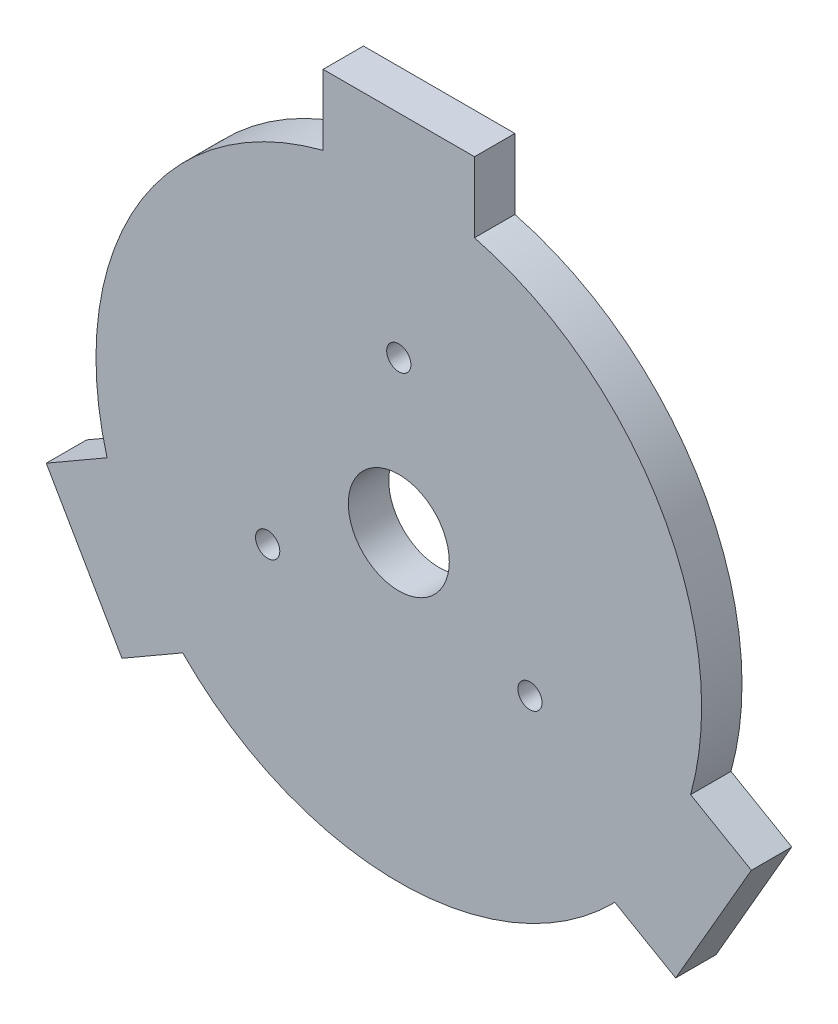
SolidWorks part; units mm, degrees
ref_plane "前视基准面" through (0, 0, 0) normal (0, 0, 1) x (1, 0, 0)
ref_plane "上视基准面" through (0, 0, 0) normal (0, 1, 0) x (1, 0, 0)
ref_plane "右视基准面" through (0, 0, 0) normal (1, 0, 0) x (0, 0, -1)
sketch "草图1" plane through (0, 0, 0) normal (0, 0, 1) x (1, 0, 0)
  line L3 (10, 28.2843) -> (10, 36)
  line L9 (-10, 36) -> (10, 36)
  line L10 (36.1769, -9.3397) -> (26.1769, -26.6603)
  line L11 (-36.1769, -9.3397) -> (-26.1769, -26.6603)
  line L12 (-29.4949, -5.4819) -> (-36.1769, -9.3397)
  line L15 (-19.4949, -22.8024) -> (-26.1769, -26.6603)
  line L17 (19.4949, -22.8024) -> (26.1769, -26.6603)
  line L20 (29.4949, -5.4819) -> (36.1769, -9.3397)
  line L24 (-10, 28.2843) -> (-10, 36)
  arc A1 (-19.4949, -22.8024) -> (19.4949, -22.8024) centre (0, 0) ccw
  circle A2 centre (0, 0) radius 5
  arc A3 (-10, 28.2843) -> (-29.4949, -5.4819) centre (0, 0) ccw
  arc A4 (29.4949, -5.4819) -> (10, 28.2843) centre (0, 0) ccw
  dimension "D10" = 60
  dimension "D2" = 10
extrude "凸台-拉伸1" add sketch "草图1" along normal blind 4
sketch "草图2" plane through (0, 0, 0) normal (0, 0, -1) x (-1, 0, 0)
  line L2 (-7.5, 28.2843) -> (-7.5, 36)
  line L3 (-7.5, 29.0474) -> (-7.5, 36)
  line L4 (-10, 36) -> (10, 36) construction
  line L5 (7.5, 36) -> (7.5, 28.2843)
  line L6 (7.5, 36) -> (7.5, 29.0474)
  line L7 (-10, 36) -> (-7.5, 36)
  line L10 (-34.9269, -11.5048) -> (-28.2449, -7.6469)
  line L11 (-34.9269, -11.5048) -> (-28.9058, -8.0285)
  line L20 (-26.1769, -26.6603) -> (-36.1769, -9.3397) construction
  line L21 (-26.1769, -26.6603) -> (-27.4269, -24.4952)
  line L22 (36.1769, -9.3397) -> (26.1769, -26.6603) construction
  line L23 (36.1769, -9.3397) -> (34.9269, -11.5048)
  line L26 (-20.7449, -20.6373) -> (-27.4269, -24.4952)
  line L27 (-21.4058, -21.0189) -> (-27.4269, -24.4952)
  line L29 (28.2449, -7.6469) -> (34.9269, -11.5048)
  line L30 (28.9058, -8.0285) -> (34.9269, -11.5048)
  line L31 (-10, 36) -> (-10, 28.2843)
  line L32 (27.4269, -24.4952) -> (20.7449, -20.6373)
  line L33 (27.4269, -24.4952) -> (21.4058, -21.0189)
  line L34 (10, 36) -> (10, 28.2843)
  line L35 (-36.1769, -9.3397) -> (-29.4949, -5.4819)
  line L36 (-26.1769, -26.6603) -> (-19.4949, -22.8024)
  line L37 (19.4949, -22.8024) -> (26.1769, -26.6603)
  line L38 (29.4949, -5.4819) -> (36.1769, -9.3397)
  line L39 (7.5, 36) -> (10, 36)
  line L40 (-34.9269, -11.5048) -> (-36.1769, -9.3397)
  line L41 (27.4269, -24.4952) -> (26.1769, -26.6603)
  arc A0 (-7.5, 29.0474) -> (-10, 28.2843) centre (0, 0) ccw
  arc A4 (10, 28.2843) -> (7.5, 29.0474) centre (0, 0) ccw
  arc A5 (-29.4949, -5.4819) -> (-28.9058, -8.0285) centre (0, 0) ccw
  arc A6 (-21.4058, -21.0189) -> (-19.4949, -22.8024) centre (0, 0) ccw
  arc A7 (19.4949, -22.8024) -> (21.4058, -21.0189) centre (0, 0) ccw
  arc A8 (28.9058, -8.0285) -> (29.4949, -5.4819) centre (0, 0) ccw
  dimension "D2" = 2.5
  dimension "D3" = 2.5
  dimension "D4" = 2.5
  dimension "D5" = 2.5
  dimension "D6" = 2.5
  dimension "D7" = 2.5
extrude "切除-拉伸1" cut sketch "草图2" against normal blind 10
sketch "草图3" plane through (0, 0, 0) normal (0, 0, -1) x (-1, 0, 0)
  circle A1 centre (0, 15) radius 1.2
  circle A2 centre (12.9904, -7.5) radius 1.2
  circle A3 centre (-12.9904, -7.5) radius 1.2
  dimension "D2" = 2.4
  dimension "D3" = 2.4
  dimension "D4" = 2.4
extrude "切除-拉伸2" cut sketch "草图3" against normal mid plane 10
